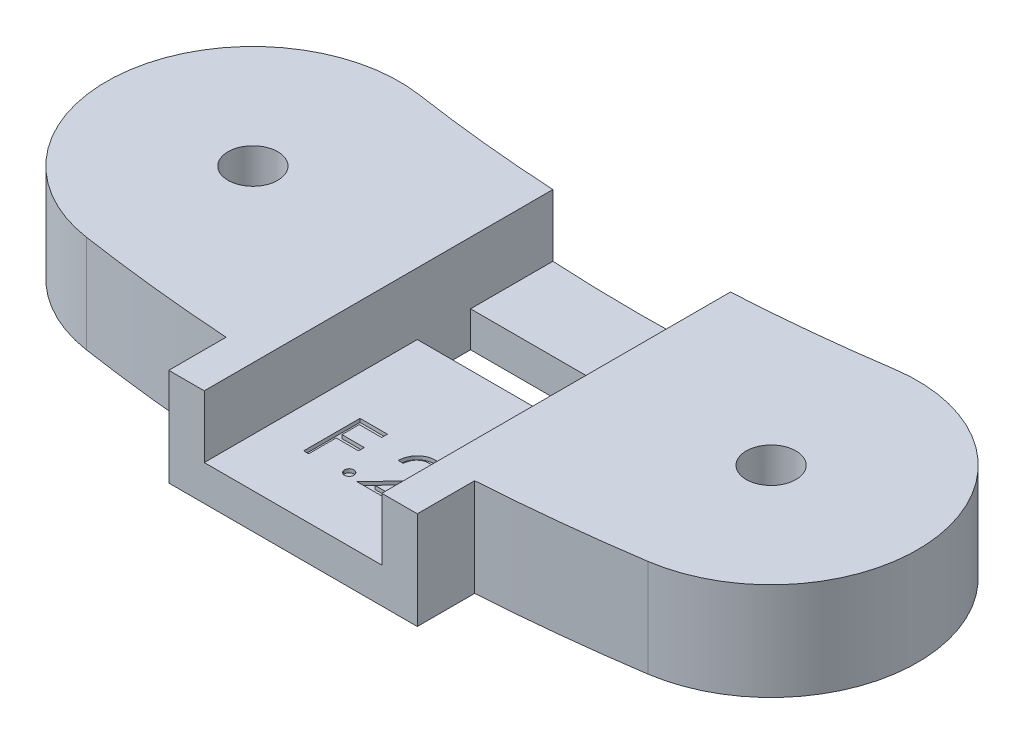
SolidWorks part; units mm, degrees
material "ABS"
ref_plane "Front Plane" through (0, 0, 0) normal (0, 0, 1) x (1, 0, 0)
ref_plane "Top Plane" through (0, 0, 0) normal (0, 1, 0) x (1, 0, 0)
ref_plane "Right Plane" through (0, 0, 0) normal (1, 0, 0) x (0, 0, -1)
sketch "Sketch2" plane through (0, 0, 0) normal (0, 1, 0) x (1, 0, 0)
  line L0 (0, 98.75) -> (0, -6.25) construction
  line L1 (0, 98.75) -> (16.169, -9.4396) construction
  line L2 (0, 98.75) -> (-14.5962, 1.0847) construction
  arc A0 (-13.3768, 9.2441) -> (13.3768, 9.2441) centre (0, 98.75) ccw
  arc A1 (-15.8156, -7.0747) -> (15.8156, -7.0747) centre (0, 98.75) ccw
  arc A2 (-33.4311, 5.8311) -> (33.4311, 5.8311) centre (0, 98.75) ccw construction
  arc A3 (-13.3768, 9.2441) -> (-15.8156, -7.0747) centre (-14.5962, 1.0847) ccw
  arc A4 (15.8156, -7.0747) -> (13.3768, 9.2441) centre (14.5962, 1.0847) ccw
  arc A8 (-18.8033, 8.1813) -> (18.8033, 8.1813) centre (0, 98.75) ccw
  arc A9 (-20.9883, -4.1309) -> (20.9883, -4.1309) centre (0, 98.75) ccw
  circle A12 centre (-14.5962, 1.0847) radius 1.4
  circle A13 centre (14.5962, 1.0847) radius 1.4
  point P0 (0, 105)
  point P4 (88.4582, 132.0444)
  point P5 (0, 105)
  point P9 (100.412, 135.699)
  point P17 (90.5, 105)
  point P22 (107, 105)
  dimension "D3" = 185
  dimension "D4" = 210
  dimension "D7" = 197.5
  dimension "D1" = 98.75
  dimension "D2" = 107
  dimension "D5" = 8.5
  dimension "D6" = 8.5
extrude "Boss-Extrude1" add sketch "Sketch2" along normal blind 14
ref_plane "Plane1" through (0, 0, 8.25) normal (0, 0, 1) x (1, 0, 0)
sketch "Sketch3" plane through (0, 0, 8.25) normal (0, 0, 1) x (1, 0, 0)
  line L0 (0, 0) -> (0, 14) construction
  line L2 (-7, 14) -> (7, 14)
  line L4 (7, 14) -> (7, 0)
  line L5 (7, 0) -> (-7, 0)
  line L6 (-7, 0) -> (-7, 14)
  line L7 (15.8156, 14) -> (-15.8156, 14) construction
  line L8 (-15.8156, 0) -> (15.8156, 0) construction
  circle A0 centre (0, 7) radius 7 construction
  circle A1 centre (0, 7) radius 3 construction
extrude "Boss-Extrude2" add sketch "Sketch3" against normal up to body and the other way blind 3 separate body contours L2 L4 L5 L6
sketch "Sketch19" plane through (0, 0, 8.25) normal (0, 0, 1) x (1, 0, 0)
  line L0 (-7, 7) -> (-33.8084, 7) construction
  line L1 (-13.3768, 14) -> (-22.8462, 14) construction
  line L3 (-13.3768, 14) -> (-22.8462, 14)
  line L4 (-7, 0) -> (-7, 14)
  line L5 (-7, 14) -> (-15.8156, 14) construction
  line L6 (-22.8462, 14) -> (-22.8462, 0)
  line L7 (-22.8462, 0) -> (-7, 0)
  line L8 (-7, 8.5) -> (-22.8462, 8.5)
  line L9 (-7, 5.5) -> (-22.8462, 5.5)
  line L10 (-7, 0) -> (-7, 14) construction
  line L11 (-7, 14) -> (-15.8156, 14)
  line L13 (-7, 8.5) -> (-33.8084, 8.5) construction
  line L14 (-7, 5.5) -> (-33.8084, 5.5) construction
  dimension "D1" = 1.5
  dimension "D2" = 1.5
extrude "Cut-Extrude4" cut sketch "Sketch19" against normal blind 22 contours L9 L4 L8 L6
ref_plane "Plane10" through (0, 0, -9.2441) normal (0, 0, 1) x (1, 0, 0)
mirror "Mirror2" about plane through (0, 0, 0) normal (1, 0, 0) of "Cut-Extrude4"
sketch "Sketch24" plane through (0, 0, 11.25) normal (0, 0, 1) x (1, 0, 0)
  line L0 (-7, 8.5) -> (-5, 8.5)
  line L1 (7, 5.5) -> (5, 5.5)
  line L2 (5, 12) -> (-5, 12)
  line L3 (-5, 12) -> (-5, 8.5)
  line L4 (-7, 14) -> (-7, 0)
  line L5 (-7, 0) -> (7, 0)
  line L6 (7, 0) -> (7, 14)
  line L7 (7, 14) -> (-7, 14)
  line L8 (-7, 14) -> (-7, 0)
  line L9 (-7, 0) -> (7, 0)
  line L10 (7, 0) -> (7, 14)
  line L11 (7, 14) -> (-7, 14)
  line L12 (-5, 2) -> (5, 2)
  line L13 (5, 2) -> (5, 5.5)
  line L14 (-5, 5.5) -> (-5, 2)
  line L15 (5, 8.5) -> (7, 8.5)
  line L16 (-5, 12) -> (-5, 2) construction
  line L17 (-5, 5.5) -> (-7, 5.5)
  line L18 (5, 8.5) -> (5, 12)
  line L20 (5, 2) -> (5, 12) construction
  line M5 (-7, 14) -> (-7, 0)
  line M7 (7, 0) -> (7, 14)
  dimension "D1" = 0
  dimension "D2" = 2
extrude "Cut-Extrude8" cut sketch "Sketch24" against normal through all contours L15 L18 L2 L3 L0 L17 L14 L12 L13 L1 M5 M7
sketch "Sketch25" plane through (0, 2, 0) normal (0, 1, 0) x (1, 0, 0)
  line L0 (-7, -11.25) -> (7, -11.25) construction
  line L1 (-5, 3.75) -> (5, 3.75)
  line L2 (-5, 0.75) -> (5, 0.75)
  line L3 (-5, 8.3882) -> (-5, -11.25) construction
  line L4 (5, 8.3882) -> (5, -11.25) construction
  line L5 (-5, 3.75) -> (-5, 0.75)
  line L6 (5, 3.75) -> (5, 0.75)
  line L8 (-7, 0.75) -> (7, 0.75) construction
  line L9 (-7, 3.75) -> (7, 3.75) construction
  dimension "D1" = 15
  dimension "D2" = 3
extrude "Cut-Extrude9" cut sketch "Sketch25" against normal blind 2
sketch "Sketch26" plane through (0, 2, 0) normal (0, 1, 0) x (1, 0, 0)
  text T0 "F.2\r\n"
extrude "Cut-Extrude10" cut sketch "Sketch26" against normal blind 0.2
